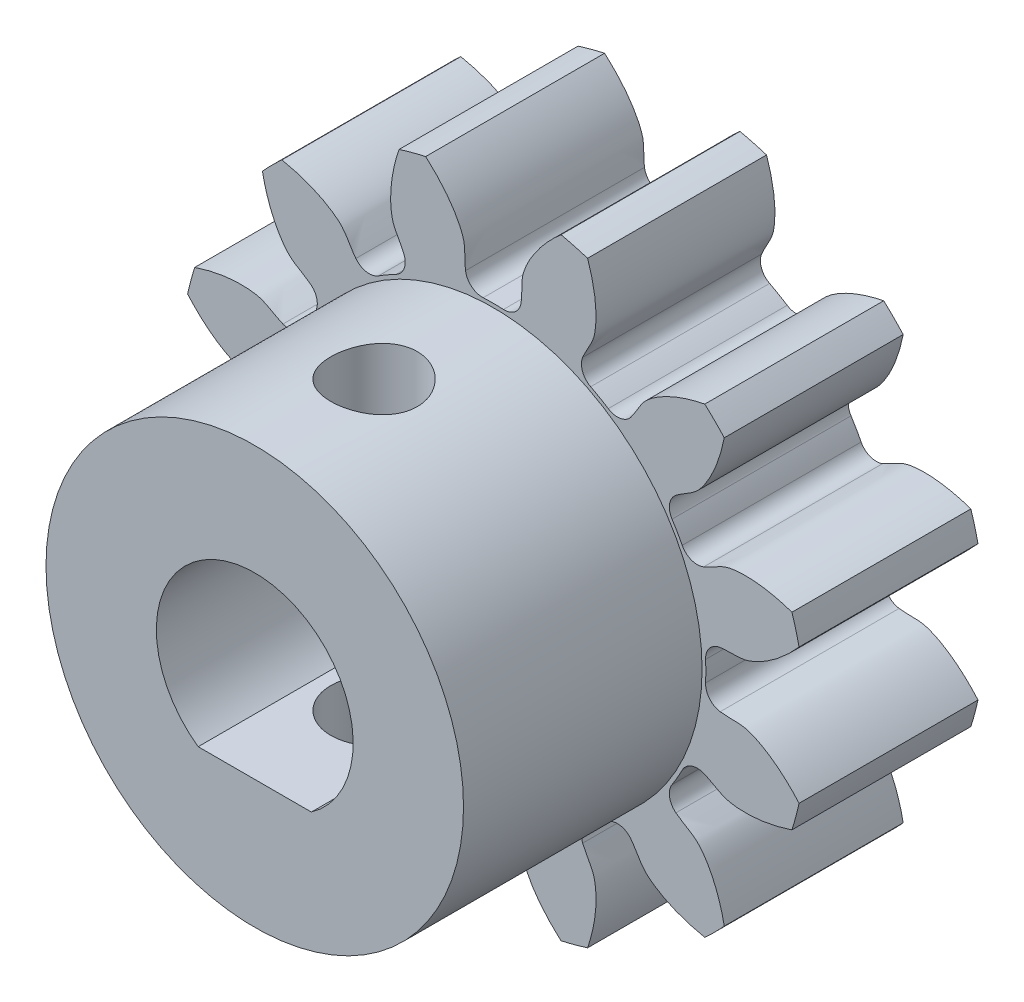
SolidWorks part; units mm, degrees
material "ABS"
ref_plane "前视基准面" through (0, 0, 0) normal (0, 0, 1) x (1, 0, 0)
ref_plane "上视基准面" through (0, 0, 0) normal (0, 1, 0) x (1, 0, 0)
ref_plane "右视基准面" through (0, 0, 0) normal (1, 0, 0) x (0, 0, -1)
ref_axis "Axis1" through (0, 0, -88.99) along (0, 0, 1)
sketch "草图1" plane through (0, 0, 0) normal (0, 0, 1) x (1, 0, 0)
  circle A0 centre (0, 0) radius 10.5
extrude "LaShenA" add sketch "草图1" along normal blind 6
sketch "SketchA" plane through (0, 0, 6) normal (0, 0, 1) x (1, 0, 0)
  line L0 (0, 0) -> (0, 10.5) construction
  arc A0 (0.3404, 7.1169) -> (-0.3404, 7.1169) centre (0, 0) ccw
  arc A1 (3.1038, 10.8739) -> (-3.1038, 10.8739) centre (0, 0) ccw
  arc A2 (-0.3404, 7.1169) -> (-0.9321, 7.607) centre (-0.3676, 7.6862) cw
  arc A3 (0.9321, 7.607) -> (0.3404, 7.1169) centre (0.3676, 7.6862) cw
  circle A4 centre (0, 0) radius 8.4572 construction
  circle A5 centre (0, 0) radius 10.5 construction
  circle A6 centre (0, 0) radius 7.125 construction
  circle A7 centre (0, 0) radius 9 construction
  spline S0 degree 3 poles (0.9321, 7.607) (0.969, 7.8699) (0.9308, 8.1755) (0.9992, 8.4847) (1.0194, 8.5511) (1.0369, 8.6035) (1.0591, 8.6633) (1.0863, 8.7302) (1.1191, 8.804) (1.1579, 8.8843) (1.2032, 8.971) (1.2554, 9.0635) (1.3149, 9.1617) (1.3821, 9.265) (1.4573, 9.3731) (1.5411, 9.4856) (1.6336, 9.602) (1.7353, 9.722) (1.8465, 9.8449) (1.9673, 9.9704) (2.0982, 10.098) (2.2393, 10.2271) (2.3909, 10.3571) (2.5532, 10.4876) (2.7885, 10.665) (2.9748, 10.7917) (3.1038, 10.8739) knots 0.119741 0.119741 0.119741 0.119741 0.289279 0.311928 0.3219 0.333685 0.347283 0.362695 0.379919 0.398957 0.419807 0.442471 0.466948 0.493238 0.521341 0.551257 0.582986 0.616529 0.651884 0.689053 0.728035 0.768829 0.811437 0.855858 0.902092 1 1 1 1
  spline S1 degree 3 poles (-0.9321, 7.607) (-0.969, 7.8699) (-0.9308, 8.1755) (-0.9992, 8.4847) (-1.0194, 8.5511) (-1.0369, 8.6035) (-1.0591, 8.6633) (-1.0863, 8.7302) (-1.1191, 8.804) (-1.1579, 8.8843) (-1.2032, 8.971) (-1.2554, 9.0635) (-1.3149, 9.1617) (-1.3821, 9.265) (-1.4573, 9.3731) (-1.5411, 9.4856) (-1.6336, 9.602) (-1.7353, 9.722) (-1.8465, 9.8449) (-1.9673, 9.9704) (-2.0982, 10.098) (-2.2393, 10.2271) (-2.3909, 10.3571) (-2.5532, 10.4876) (-2.7885, 10.665) (-2.9748, 10.7917) (-3.1038, 10.8739) knots 0.119741 0.119741 0.119741 0.119741 0.289279 0.311928 0.3219 0.333685 0.347283 0.362695 0.379919 0.398957 0.419807 0.442471 0.466948 0.493238 0.521341 0.551257 0.582986 0.616529 0.651884 0.689053 0.728035 0.768829 0.811437 0.855858 0.902092 1 1 1 1
  dimension "D1" = 0.57
  dimension "Db" = 16.9145
  dimension "Da" = 21
  dimension "Df" = 14.25
  dimension "Dn" = 18
extrude "Cut-ExtrudeA" cut sketch "SketchA" against normal blind 6
pattern_circular "www.KYTool.cn" count 12 over 360 about axis through (0, 0, -88.99) along (0, 0, 1) of "Cut-ExtrudeA"
sketch "草图3" plane through (0, 0, 6) normal (0, 0, 1) x (1, 0, 0)
  line L0 (1.8974, -2.7) -> (-1.8974, -2.7)
  circle A0 centre (0, 0) radius 3.3
  circle A1 centre (0, 0) radius 7
  dimension "D1" = 6.6
  dimension "D2" = 14
  dimension "D3" = 2.7
extrude "凸台-拉伸2" add sketch "草图3" along normal blind 8 contours A1 A0 | L0 A0
sketch "草图4" plane through (0, 0, 6) normal (0, 0, 1) x (1, 0, 0)
  line L0 (1.8974, -2.7) -> (-1.8974, -2.7) construction
  line L1 (1.8974, -2.7) -> (-1.8974, -2.7)
  arc A0 (1.8974, -2.7) -> (-1.8974, -2.7) centre (0, 0) ccw construction
  arc A1 (1.8974, -2.7) -> (-1.8974, -2.7) centre (0, 0) ccw
extrude "切除-拉伸2" cut sketch "草图4" against normal through all
sketch "草图5" plane through (0, -2.7, 0) normal (0, 1, 0) x (1, 0, 0)
  line L0 (-7, -14) -> (7, -14) construction
  circle A0 centre (0, -10) radius 1.45
  dimension "D1" = 2.9
  dimension "D2" = 4
extrude "切除-拉伸3" cut sketch "草图5" against normal through all both and the other way through all
